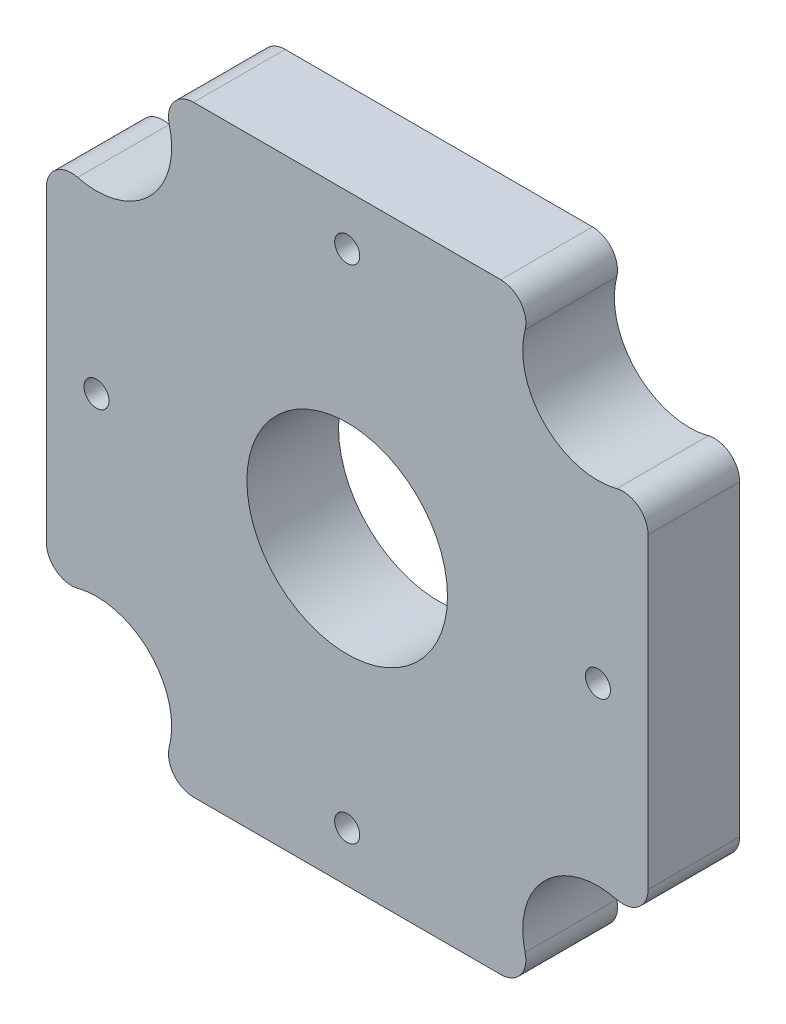
SolidWorks part; units mm, degrees
material "Balsa"
ref_plane "Front Plane" through (0, 0, 0) normal (0, 0, 1) x (1, 0, 0)
ref_plane "Top Plane" through (0, 0, 0) normal (0, 1, 0) x (1, 0, 0)
ref_plane "Right Plane" through (0, 0, 0) normal (1, 0, 0) x (0, 0, -1)
sketch "Sketch1" plane through (0, 0, 0) normal (0, 0, 1) x (1, 0, 0)
  line L0 (0, 0) -> (0, 19.05) construction
  line L1 (12.3252, 19.05) -> (-12.3252, 19.05)
  line L2 (0, 0) -> (-19.05, 19.05) construction
  line L3 (-19.05, 12.3252) -> (-19.05, -12.3252)
  line L4 (-19.05, 0) -> (0, 0) construction
  line L5 (-12.3252, 19.05) -> (-19.05, 19.05) construction
  line L6 (-19.05, 19.05) -> (-19.05, 12.3252) construction
  line L7 (19.05, 12.3252) -> (19.05, -12.3252)
  line L8 (12.3252, -19.05) -> (-12.3252, -19.05)
  arc A0 (-12.3252, 19.05) -> (-19.05, 12.3252) centre (-15.875, 15.875) cw
  arc A1 (12.3252, 19.05) -> (19.05, 12.3252) centre (15.875, 15.875) ccw
  arc A2 (12.3252, -19.05) -> (19.05, -12.3252) centre (15.875, -15.875) cw
  arc A3 (-12.3252, -19.05) -> (-19.05, -12.3252) centre (-15.875, -15.875) ccw
  point P18 (19.05, 0)
  dimension "D3" = 4.7625
  dimension "D1" = 3.175
  dimension "D2" = 19.05
extrude "Boss-Extrude1" add sketch "Sketch1" along normal blind 5.8
sketch "Sketch2" plane through (0, 0, 5.8) normal (0, 0, 1) x (1, 0, 0)
  line L0 (19.05, 0) -> (-19.05, 0) construction
  line L1 (19.05, -12.3252) -> (19.05, 12.3252) construction
  line L2 (-19.05, 12.3252) -> (-19.05, -12.3252) construction
  line L3 (0, 0) -> (0, 15.875) construction
  line L5 (12.3252, 19.05) -> (-12.3252, 19.05) construction
  circle A0 centre (0, 15.875) radius 0.7937
  circle A1 centre (15.875, 0) radius 0.7937
  circle A2 centre (0, -15.875) radius 0.7937
  circle A3 centre (-15.875, 0) radius 0.7937
  dimension "D1" = 1.5875
  dimension "D2" = 3.175
  dimension "D3" = 4
extrude "Cut-Extrude1" cut sketch "Sketch2" against normal through all
sketch "Sketch3" plane through (0, 0, 5.8) normal (0, 0, 1) x (1, 0, 0)
  circle A0 centre (0, 0) radius 6.35
  dimension "D1" = 12.7
extrude "Cut-Extrude2" cut sketch "Sketch3" against normal blind 12.7
fillet "Fillet1" radius 1.5875 8 edges at (19.05, -12.3252, 2.9) (-19.05, -12.3252, 2.9) (-12.3252, -19.05, 2.9) (12.3252, -19.05, 2.9) (19.05, 12.3252, 2.9) (12.3252, 19.05, 2.9) (-12.3252, 19.05, 2.9) (-19.05, 12.3252, 2.9)
